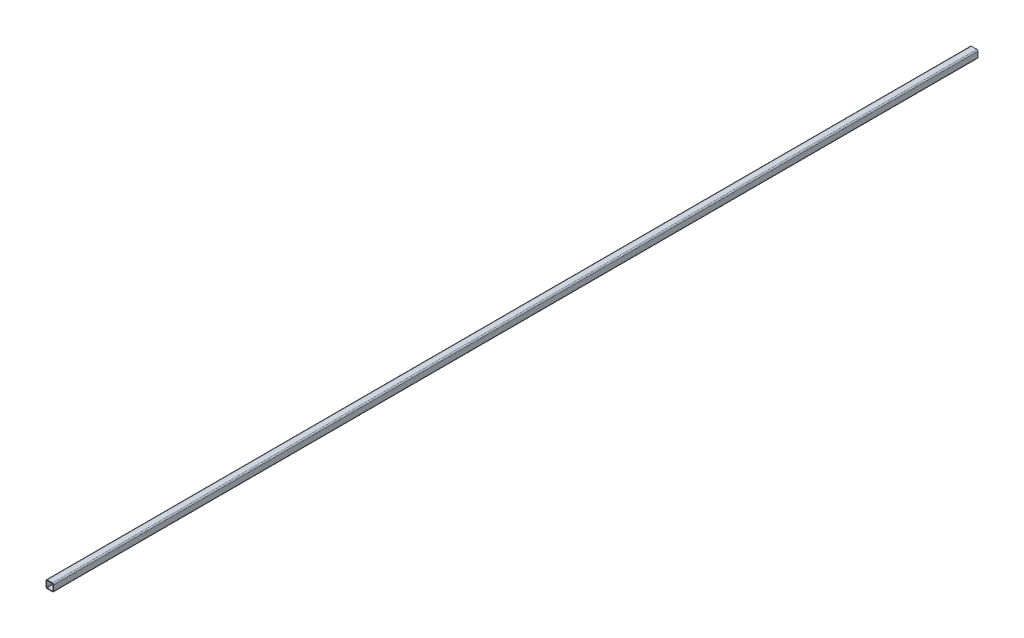
SolidWorks part; units mm, degrees
material "AISI 316 Annealed Stainless Steel Bar (SS)"
ref_plane "Front Plane" through (0, 0, 0) normal (0, 0, 1) x (1, 0, 0)
ref_plane "Top Plane" through (0, 0, 0) normal (0, 1, 0) x (1, 0, 0)
ref_plane "Right Plane" through (0, 0, 0) normal (1, 0, 0) x (0, 0, -1)
sketch "Sketch1" plane through (0, 0, 0) normal (0, 0, 1) x (1, 0, 0)
  line L1 (1, 2) -> (9.7, 2)
  line L2 (-1, 0) -> (-1, -8.7)
  line L3 (1, -10.7) -> (9.7, -10.7)
  line L4 (11.7, 0) -> (11.7, -8.7)
  line L7 (9.7, 1) -> (1, 1)
  line L8 (10.7, 0) -> (10.7, -8.7)
  line L9 (9.7, -9.7) -> (1, -9.7)
  line L10 (0, 0) -> (0, -8.7)
  arc A0 (-1, -8.7) -> (1, -10.7) centre (1, -8.7) ccw
  arc A1 (1, 2) -> (-1, 0) centre (1, 0) ccw
  arc A2 (11.7, 0) -> (9.7, 2) centre (9.7, 0) ccw
  arc A3 (9.7, -10.7) -> (11.7, -8.7) centre (9.7, -8.7) ccw
  arc A4 (1, 1) -> (0, 0) centre (1, 0) ccw
  arc A5 (0, -8.7) -> (1, -9.7) centre (1, -8.7) ccw
  arc A6 (9.7, -9.7) -> (10.7, -8.7) centre (9.7, -8.7) ccw
  arc A7 (10.7, 0) -> (9.7, 1) centre (9.7, 0) ccw
  point P0 (0, 0)
  point P7 (0, 0)
  dimension "D2" = 12.7
  dimension "D3" = 2
  dimension "D8" = 1
  dimension "D1" = 12.7
  dimension "D4" = 1
  dimension "D5" = 1
  dimension "D6" = 1
  dimension "D7" = 1
extrude "Boss-Extrude1" add sketch "Sketch1" along normal blind 1524
